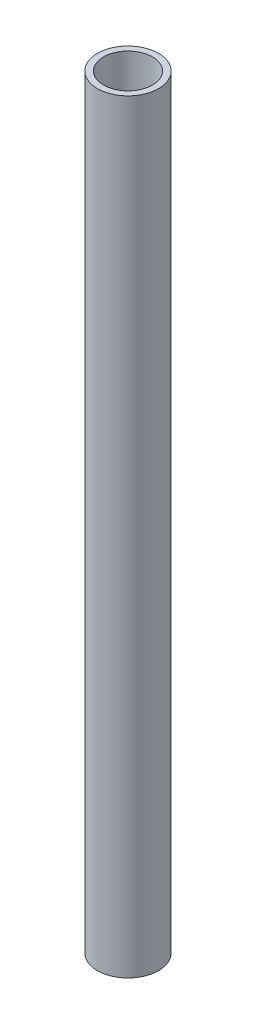
SolidWorks part; units mm, degrees
ref_plane "Front Plane" through (0, 0, 0) normal (0, 0, 1) x (1, 0, 0)
ref_plane "Top Plane" through (0, 0, 0) normal (0, 1, 0) x (1, 0, 0)
ref_plane "Right Plane" through (0, 0, 0) normal (1, 0, 0) x (0, 0, -1)
sketch "Sketch1" plane through (0, 0, 0) normal (0, 1, 0) x (1, 0, 0)
  circle A0 centre (0, 0) radius 4
  dimension "D1" = 8
extrude "Boss-Extrude1" add sketch "Sketch1" against normal blind 100
sketch "Sketch3" plane through (0, 0, 0) normal (0, 1, 0) x (1, 0, 0)
  circle A0 centre (0, 0) radius 3.2
  dimension "D1" = 6.4
extrude "Cut-Extrude3" cut sketch "Sketch3" against normal through all
